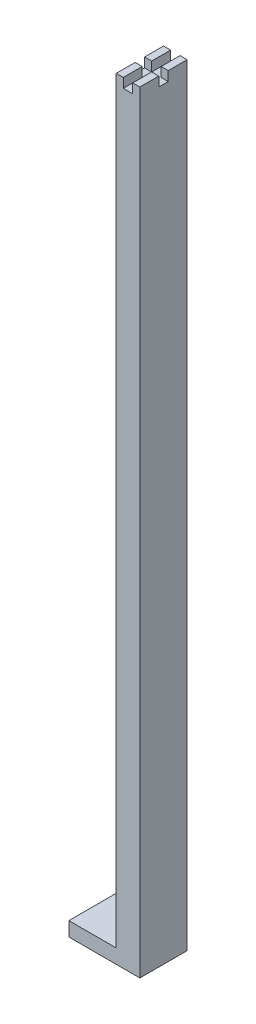
SolidWorks part; units mm, degrees
ref_plane "Front Plane" through (0, 0, 0) normal (0, 0, 1) x (1, 0, 0)
ref_plane "Top Plane" through (0, 0, 0) normal (0, 1, 0) x (1, 0, 0)
ref_plane "Right Plane" through (0, 0, 0) normal (1, 0, 0) x (0, 0, -1)
sketch "Sketch1" plane through (0, 0, 0) normal (0, 1, 0) x (1, 0, 0)
  line L1 (7.5, -5) -> (-7.5, -5)
  line L2 (7.5, -5) -> (7.5, 5)
  line L3 (7.5, 5) -> (-7.5, 5)
  line L4 (-7.5, -5) -> (-7.5, 5)
  line L5 (7.5, -5) -> (-7.5, 5) construction
  line L6 (7.5, 5) -> (-7.5, -5) construction
  point P0 (0, 0)
  dimension "D1" = 15
  dimension "D2" = 10
extrude "Boss-Extrude1" add sketch "Sketch1" along normal blind 3
ref_plane "Plane1" through (0, 3, 0) normal (0, 1, 0) x (1, 0, 0)
sketch "Sketch2" plane through (0, 3, 0) normal (0, 1, 0) x (1, 0, 0)
  line L0 (-7.5, -5) -> (7.5, -5) construction
  line L1 (7.5, 5) -> (2.5, 5)
  line L2 (7.5, 5) -> (7.5, -5)
  line L3 (7.5, -5) -> (2.5, -5)
  line L4 (2.5, 5) -> (2.5, -5)
  dimension "D1" = 5
extrude "Boss-Extrude2" add sketch "Sketch2" along normal blind 160
ref_plane "Plane6" through (0, 163, 0) normal (0, 1, 0) x (1, 0, 0)
sketch "Sketch3" plane through (0, 163, 0) normal (0, 1, 0) x (1, 0, 0)
  line L0 (4, -1) -> (2.5, -1)
  line L1 (7.5, 5) -> (2.5, 5) construction
  line L2 (2.5, -5) -> (7.5, -5) construction
  line L3 (2.5, 0) -> (4, 0) construction
  line L4 (2.5, 5) -> (2.5, -5) construction
  line L6 (2.5, 5) -> (2.5, -5) construction
  line L7 (6, -5) -> (4, -5)
  line L8 (6, -5) -> (6, -1)
  line L9 (6, 5) -> (4, 5)
  line L10 (4, -5) -> (4, -1)
  line L12 (6, 5) -> (5.2, 1) construction
  line L13 (7.5, -1) -> (6, -1)
  line L14 (7.5, -1) -> (7.5, 1)
  line L15 (7.5, 1) -> (6, 1)
  line L16 (2.5, -1) -> (2.5, 1)
  line L17 (7.5, -1) -> (6, -0.4) construction
  line L21 (5, -1) -> (5, -5) construction
  line L22 (4, 1) -> (2.5, 1)
  line L23 (4.8, 1) -> (4, 5) construction
  line L24 (4, 1) -> (4, 5)
  line L26 (5, 0) -> (4, 0.4) construction
  line L27 (6, 1) -> (6, 5)
  line L28 (5, 0) -> (4, -0.4) construction
  point P12 (5, 0)
  point P17 (5, 0)
  dimension "D1" = 2
  dimension "D2" = 2
extrude "Cut-Extrude1" cut sketch "Sketch3" against normal blind 2
